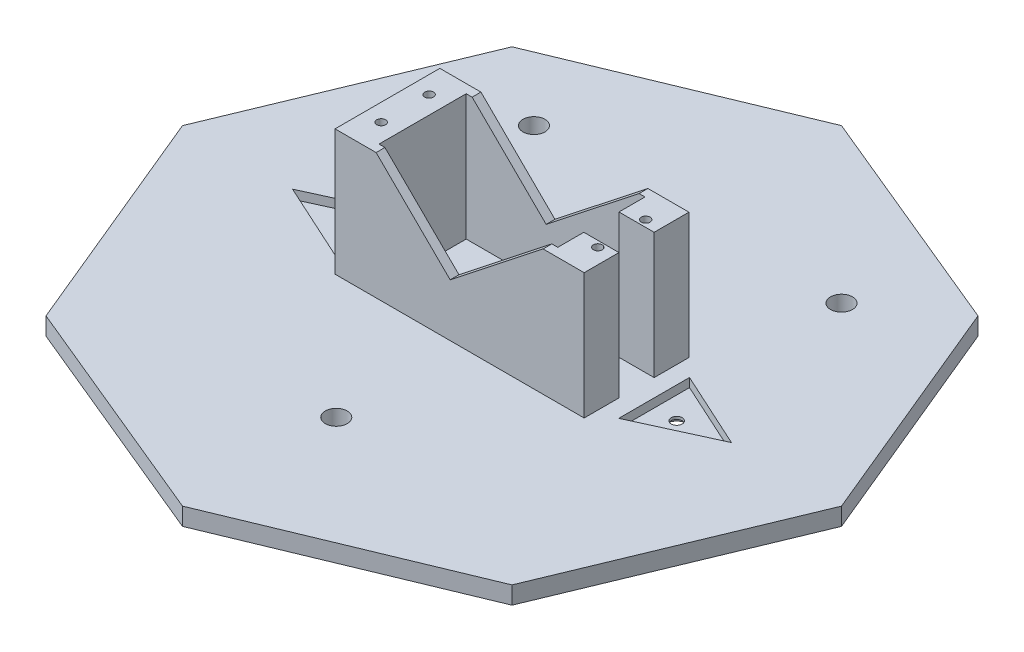
SolidWorks part; units mm, degrees
ref_plane "Ebene vorne" through (0, 0, 0) normal (0, 0, 1) x (1, 0, 0)
ref_plane "Ebene oben" through (0, 0, 0) normal (0, 1, 0) x (1, 0, 0)
ref_plane "Ebene rechts" through (0, 0, 0) normal (1, 0, 0) x (0, 0, -1)
sketch "Skizze2" plane through (0, 0, 0) normal (0, 1, 0) x (1, 0, 0)
  line L0 (-75, 0) -> (75, 0) construction
  line L1 (-55, 0) -> (55, 0) construction
  line L2 (0, -55) -> (0, 55) construction
  line L3 (-53.033, -53.033) -> (53.033, 53.033)
  line L4 (53.033, -53.033) -> (-53.033, 53.033)
  line L5 (-75, 0) -> (-53.033, 53.033)
  line L6 (-53.033, 53.033) -> (0, 75)
  line L7 (0, 75) -> (53.033, 53.033)
  line L8 (75, 0) -> (53.033, 53.033)
  line L9 (75, 0) -> (53.033, -53.033)
  line L10 (53.033, -53.033) -> (0, -75)
  line L11 (0, -75) -> (-53.033, -53.033)
  line L12 (-75, 0) -> (-53.033, -53.033)
  point P10 (0, 0)
  point P13 (0, 0)
  dimension "D1" = 150
  dimension "D2" = 75
  dimension "D3" = 150
  dimension "D4" = 150
  dimension "D5" = 45
  dimension "D6" = 45
  dimension "D7" = 75
  dimension "D8" = 75
extrude "Aufsatz-Linear austragen1" add sketch "Skizze2" along normal blind 3 and the other way blind 1 contours L7 L6 L4 L3 | L3 L0 L8 | L0 L4 L9 | L11 L10 L4 L3 | L5 L0 L4 | L0 L12 L3
sketch "Skizze5" plane through (0, 0, 0) normal (0, 1, 0) x (1, 0, 0)
  line L0 (20.35, -4) -> (28.35, -4)
  line L1 (-20.35, -9.925) -> (20.35, -9.925)
  line L2 (-20.35, -9.925) -> (-20.35, 9.925)
  line L3 (-20.35, 9.925) -> (20.35, 9.925)
  line L4 (20.35, -9.925) -> (20.35, -4)
  line L5 (-20.35, -9.925) -> (20.35, 9.925) construction
  line L6 (-20.35, 9.925) -> (20.35, -9.925) construction
  line L7 (-28.35, -11.925) -> (28.35, -11.925)
  line L8 (-28.35, -11.925) -> (-28.35, 11.925)
  line L9 (-28.35, 11.925) -> (28.35, 11.925)
  line L10 (28.35, -11.925) -> (28.35, -4)
  line L11 (-28.35, -11.925) -> (28.35, 11.925) construction
  line L12 (-28.35, 11.925) -> (28.35, -11.925) construction
  line L13 (20.35, 4) -> (28.35, 4)
  line L14 (-1.65, 0) -> (1.65, 0) construction
  line L15 (20.35, 4) -> (20.35, 9.925)
  line L16 (28.35, 4) -> (28.35, 11.925)
  point P0 (0, 0)
  point P6 (0, 0)
  dimension "D1" = 40.7
  dimension "D2" = 19.85
  dimension "D3" = 2
  dimension "D4" = 8
  dimension "D5" = 4
  dimension "D6" = 4
extrude "Aufsatz-Linear austragen3" add sketch "Skizze5" along normal blind 31.65
sketch "Skizze6" plane through (0, 0, 11.925) normal (0, 0, 1) x (1, 0, 0)
  line L0 (-19, 31.65) -> (19, 31.65)
  line L1 (-28.35, 31.65) -> (28.35, 31.65) construction
  line L2 (19, 31.65) -> (-2.1527, 14.9945)
  line L3 (-2.1527, 14.9945) -> (-19, 31.65)
  line L4 (0, -55) -> (0, 55) construction
  point P5 (0, 31.65)
  dimension "D1" = 38
  dimension "D2" = 0
extrude "Schnitt-Linear austragen1" cut sketch "Skizze6" against normal blind 28.65
sketch "Skizze7" plane through (0, 3, 0) normal (0, 1, 0) x (1, 0, 0)
  line L5 (-35, -40) -> (33.3537, 38.1186) construction
  line L6 (-33.3537, 38.1186) -> (35, -40) construction
  circle A0 centre (35, 40) radius 2.5
  circle A1 centre (-35, 40) radius 2.5
  circle A2 centre (0, -40) radius 2.5
  point P0 (0, 0)
  dimension "D3" = 5
  dimension "D4" = 5
  dimension "D5" = 5
  dimension "D1" = 80
  dimension "D2" = 70
extrude "Schnitt-Linear austragen2" cut sketch "Skizze7" against normal through all
sketch "Skizze8" plane through (0, 3, 0) normal (0, 1, 0) x (1, 0, 0)
  line L0 (-75, 0) -> (75, 0) construction
  line L7 (-32.35, 8.05) -> (-32.35, -8.05)
  line L8 (-44.0833, 2.6833) -> (-32.35, -8.05) construction
  line L9 (-44.0833, -2.6833) -> (-32.35, 8.05) construction
  line L12 (32.35, 8.05) -> (32.35, -8.05)
  line L15 (32.35, 8.05) -> (44.0833, -2.6833) construction
  line L16 (32.35, -8.05) -> (44.0833, 2.6833) construction
  line L17 (28.35, -11.925) -> (28.35, -4) construction
  line L18 (-28.35, 11.925) -> (-28.35, -11.925) construction
  line L19 (-49.95, 0) -> (-32.35, -8.05)
  line L21 (-32.35, 8.05) -> (-49.95, 0)
  line L22 (32.35, -8.05) -> (49.95, 0)
  line L23 (49.95, 0) -> (32.35, 8.05)
  line L24 (32.35, -8.05) -> (32.35, 8.05)
  point P2 (-41.15, 0)
  point P7 (41.15, 0)
  dimension "D1" = 4
  dimension "D2" = 4
  dimension "D3" = 16.1
extrude "Schnitt-Linear austragen6" cut sketch "Skizze8" against normal blind 2 contours L7 L21 L19 | L22 L23 L12
sketch "Skizze9" plane through (0, 31.65, 0) normal (0, 1, 0) x (1, 0, 0)
  circle A0 centre (-24.4, -5.375) radius 1
  circle A1 centre (-24.4, 5.525) radius 1
  circle A2 centre (24.9, 5.525) radius 1
  circle A3 centre (24.9, -5.375) radius 1
  dimension "D1" = 2
  dimension "D2" = 2
  dimension "D3" = 2
  dimension "D4" = 2
extrude "Schnitt-Linear austragen5" cut sketch "Skizze9" against normal blind 13.1
sketch "Skizze10" plane through (0, 1, 0) normal (0, 1, 0) x (1, 0, 0)
  line L1 (-0.013, 21.1078) -> (0.0218, -30.9037) construction
  line L7 (41.9977, 0.05) -> (22.7023, 0.05) construction
  line L8 (-28.35, 11.925) -> (-28.35, -11.925) construction
  line L9 (28.35, 4) -> (28.35, 11.925) construction
  circle A0 centre (-37.4378, 0) radius 1.25
  circle A1 centre (37.44, 0.05) radius 1.25
  point P6 (0, 0)
  dimension "D1" = 2.5
  dimension "D2" = 0
  dimension "D3" = 9.0878
  dimension "D4" = 9.09
extrude "Schnitt-Linear austragen7" cut sketch "Skizze10" against normal through all
sketch "Skizze11" plane through (0, -1, 0) normal (0, -1, 0) x (1, 0, 0)
  circle A0 centre (-37.4378, 0) radius 2.75
  circle A1 centre (37.44, -0.05) radius 2.75
  dimension "D1" = 5.5
  dimension "D2" = 5.5
extrude "Schnitt-Linear austragen8" cut sketch "Skizze11" against normal blind 1.4
